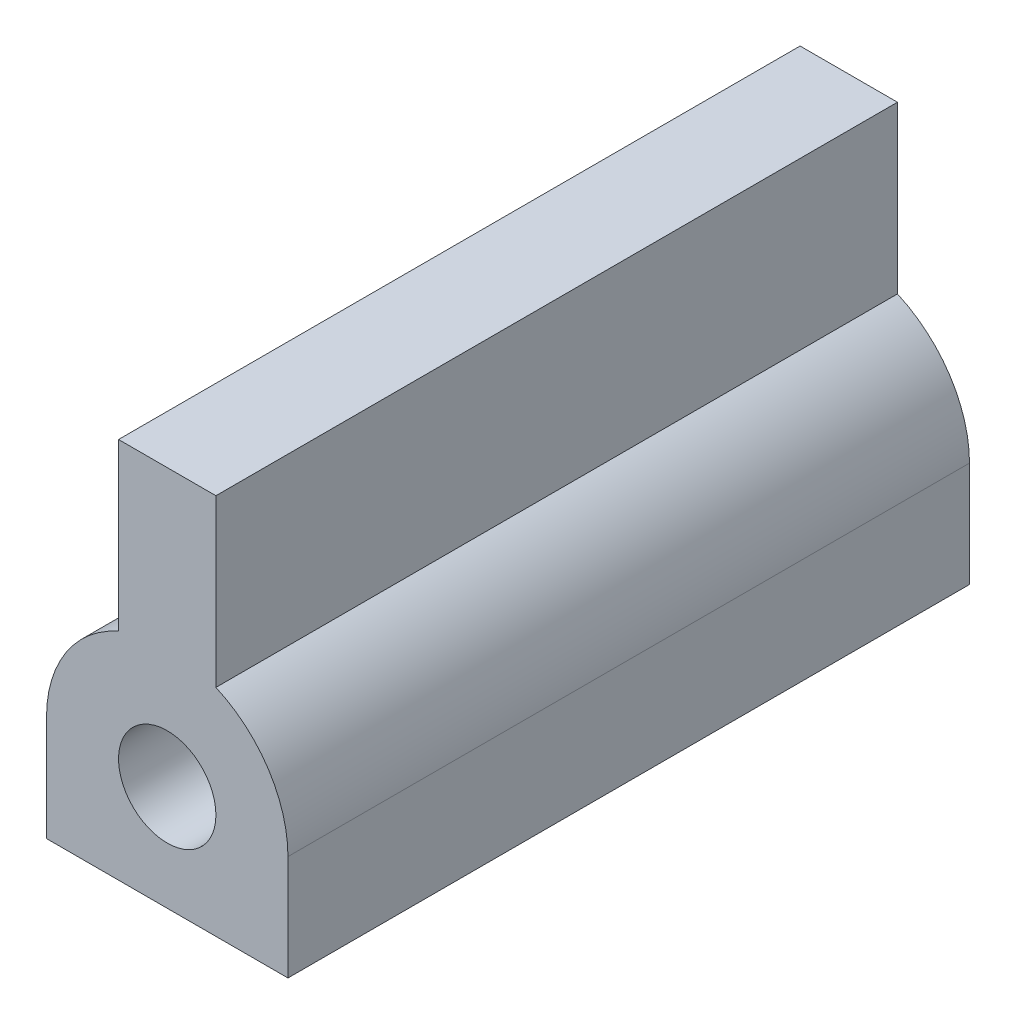
SolidWorks part; units mm, degrees
ref_plane "Front Plane" through (0, 0, 0) normal (0, 0, 1) x (1, 0, 0)
ref_plane "Top Plane" through (0, 0, 0) normal (0, 1, 0) x (1, 0, 0)
ref_plane "Right Plane" through (0, 0, 0) normal (1, 0, 0) x (0, 0, -1)
sketch "Sketch1" plane through (0, 0, 0) normal (0, 0, 1) x (1, 0, 0)
  line L0 (7.874, -6.858) -> (-7.874, -6.858)
  line L1 (-7.874, -6.858) -> (-7.874, 0)
  line L2 (7.874, 0) -> (7.874, -6.858)
  line L3 (-3.175, 7.2055) -> (-3.175, 18.034)
  line L4 (-3.175, 18.034) -> (3.175, 18.034)
  line L5 (3.175, 18.034) -> (3.175, 7.2055)
  line L6 (0, 18.034) -> (0, -6.858) construction
  arc A0 (-7.874, 0) -> (-3.175, 7.2055) centre (0, 0) cw
  circle A1 centre (0, 0) radius 3.175
  arc A2 (3.175, 7.2055) -> (7.874, 0) centre (0, 0) cw
  dimension "D1" = 6.35
  dimension "D2" = 15.748
  dimension "D3" = 24.892
  dimension "D4" = 6.858
  dimension "D5" = 6.35
extrude "Boss-Extrude1" add sketch "Sketch1" along normal mid plane 44.45
